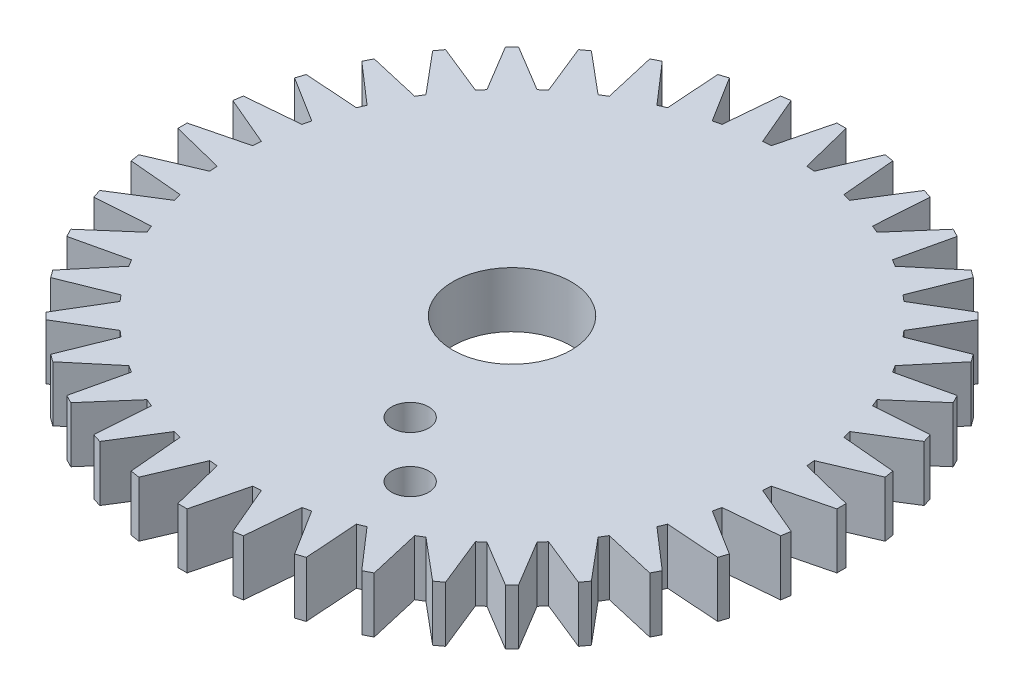
SolidWorks part; units mm, degrees
material "Acrylic (Medium-high impact)"
ref_plane "Front Plane" through (0, 0, 0) normal (0, 0, 1) x (1, 0, 0)
ref_plane "Top Plane" through (0, 0, 0) normal (0, 1, 0) x (1, 0, 0)
ref_plane "Right Plane" through (0, 0, 0) normal (1, 0, 0) x (0, 0, -1)
sketch "Sketch1" plane through (0, 0, 0) normal (0, 1, 0) x (1, 0, 0)
  circle A0 centre (0, 0) radius 15
  dimension "D1" = 30
extrude "Boss-Extrude1" add sketch "Sketch1" along normal blind 3
sketch "Sketch2" plane through (0, 3, 0) normal (0, 1, 0) x (1, 0, 0)
  line L0 (0, 0) -> (0, 20.3153) construction
sketch "Sketch3" plane through (0, 3, 0) normal (0, 1, 0) x (1, 0, 0)
  line L0 (-1, 14.8) -> (-0.25, 17.8)
  line L1 (-0.25, 17.8) -> (0.25, 17.8)
  line L2 (-1, 14.8) -> (1, 14.8)
  line L3 (0, 14.8) -> (0, 17.7311) construction
  line L4 (1, 14.8) -> (0.25, 17.8)
  point P8 (0, 17.8)
  dimension "D1" = 0.5
  dimension "D2" = 3
  dimension "D3" = 2
  dimension "D4" = 14.8
extrude "Boss-Extrude2" add sketch "Sketch3" against normal blind 3
pattern_circular "CirPattern1" count 40 every 9 about axis through (0, 0, 0) along (0, 1, 0) of "Boss-Extrude2"
sketch "Sketch4" plane through (0, 3, 0) normal (0, 1, 0) x (1, 0, 0)
  circle A0 centre (0, 0) radius 3.2
  dimension "D1" = 6.4
extrude "Cut-Extrude1" cut sketch "Sketch4" against normal blind 3
sketch "Sketch5" plane through (0, 3, 0) normal (0, 1, 0) x (1, 0, 0)
  line L0 (0, 13.8218) -> (0, -11.1513) construction
  line L1 (0, -11.1513) -> (0, -12.8114) construction
  circle A0 centre (2, -7.5) radius 1
  circle A2 centre (5, -10.5) radius 1
  dimension "D1" = 2
  dimension "D3" = 7.5
  dimension "D4" = 2
  dimension "D2" = 2
  dimension "D5" = 5
  dimension "D6" = 3
extrude "Cut-Extrude2" cut sketch "Sketch5" against normal blind 3
